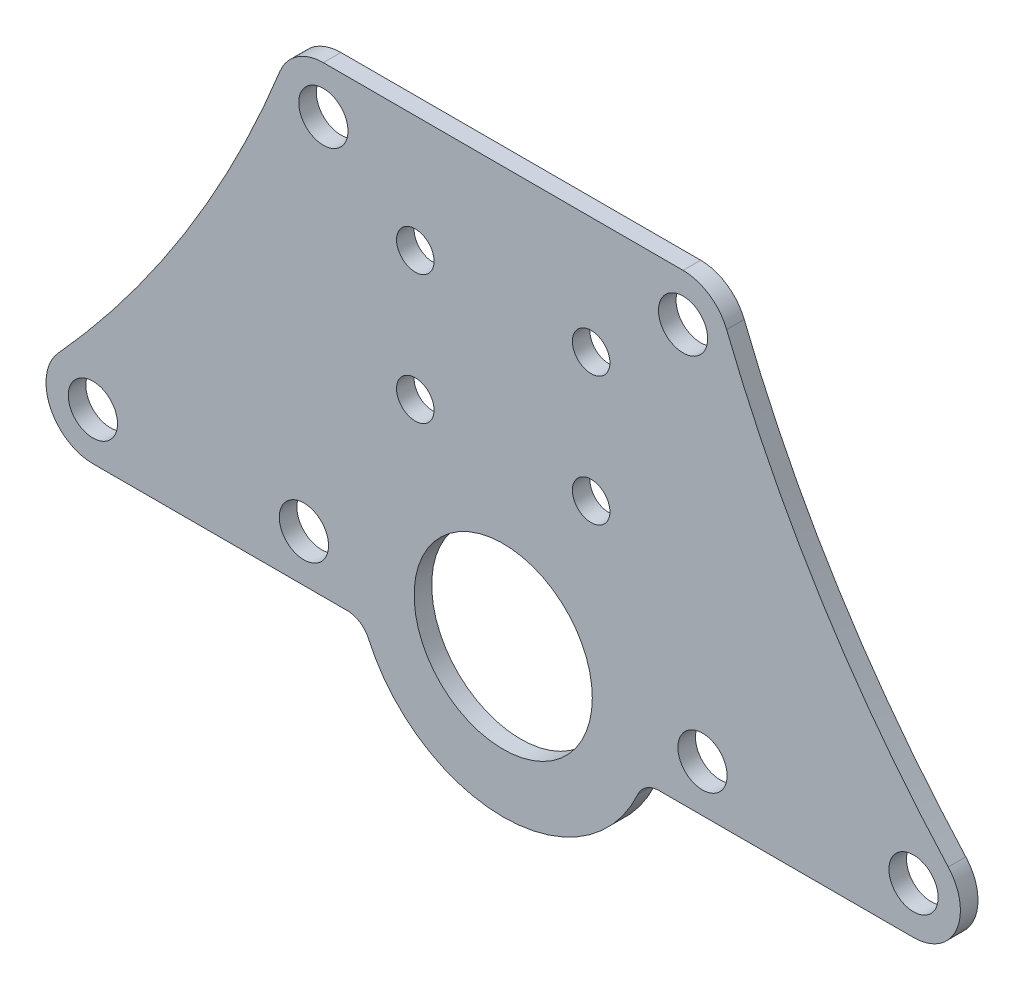
SolidWorks part; units mm, degrees
material "5052-H34"
ref_plane "正面" through (0, 0, 0) normal (0, 0, 1) x (1, 0, 0)
ref_plane "平面" through (0, 0, 0) normal (0, 1, 0) x (1, 0, 0)
ref_plane "右側面" through (0, 0, 0) normal (1, 0, 0) x (0, 0, -1)
sketch "ｽｹｯﾁ1" plane through (0, 0, 0) normal (0, 0, 1) x (1, 0, 0)
  line L0 (0, 5.5) -> (0, 0) construction
  line L1 (-7.5, 5.5) -> (7.5, 5.5) construction
  line L2 (-7.5, 5.5) -> (-7.5, -5.5) construction
  line L3 (-7.5, -5.5) -> (7.5, -5.5) construction
  line L4 (7.5, 5.5) -> (7.5, -5.5) construction
  line L5 (-7.5, 5.5) -> (7.5, -5.5) construction
  line L6 (-7.5, -5.5) -> (7.5, 5.5) construction
  line L7 (0, 0) -> (7.5, 0) construction
  line L8 (0, 0) -> (0, -20) construction
  line L9 (0, -12.5) -> (0, 29.8609) construction
  line L10 (0, -20) -> (35, -20) construction
  line L11 (0, -20) -> (15.343, 11.4578) construction
  line L12 (0, -20) -> (111.9546, 49.957) construction
  line L13 (-35, -24) -> (0, -24)
  line L14 (-15.343, 15.4578) -> (15.343, 15.4578)
  line L15 (0, -24) -> (35, -24)
  circle A0 centre (7.5, 5.5) radius 1.6
  circle A1 centre (-7.5, 5.5) radius 1.6
  circle A2 centre (7.5, -5.5) radius 1.6
  circle A3 centre (-7.5, -5.5) radius 1.6
  circle A4 centre (0, -20) radius 7.6
  circle A5 centre (0, -20) radius 30 construction
  arc A6 (0, 15) -> (5.9222, 14.4953) centre (0, -20) ccw construction
  circle A7 centre (35, -20) radius 2.1
  circle A8 centre (-35, -20) radius 2.1
  circle A9 centre (15.343, 11.4578) radius 2.1
  circle A10 centre (-15.343, 11.4578) radius 2.1
  arc A11 (34.7714, -23.9935) -> (37.9598, -17.3093) centre (35, -20) ccw
  arc A12 (19.0588, 12.9385) -> (14.7529, 15.414) centre (15.343, 11.4578) ccw
  arc A13 (-34.7714, -23.9935) -> (-37.9598, -17.3093) centre (-35, -20) cw
  arc A14 (-19.0588, 12.9385) -> (-14.7529, 15.414) centre (-15.343, 11.4578) cw
  arc A15 (19.0588, 12.9385) -> (37.9598, -17.3093) centre (111.9546, 49.957) ccw
  circle A16 centre (17, -20) radius 2.1
  arc A17 (-19.0588, 12.9385) -> (-37.9598, -17.3093) centre (-111.9546, 49.957) cw
  arc A18 (5.9222, 14.4953) -> (14.7529, 15.414) centre (0, 114.3198) ccw construction
  arc A19 (0, 214.3198) -> (-14.7529, 15.414) centre (0, 114.3198) ccw construction
  arc A20 (60.5335, 193.9169) -> (0, 214.3198) centre (0, 114.3198) ccw construction
  arc A21 (14.7529, 15.414) -> (-14.7529, 15.414) centre (0, 114.3198) ccw construction
  arc A22 (-14.7529, 15.414) -> (60.5335, 193.9169) centre (0, 114.3198) ccw construction
  circle A24 centre (0, -20) radius 12.6
  circle A27 centre (-17, -20) radius 2.1
  arc A30 (-14.7529, 15.414) -> (-5.9222, 14.4953) centre (0, 114.3198) ccw construction
  arc A31 (-5.9222, 14.4953) -> (0, 14.3198) centre (0, 114.3198) ccw construction
  arc A32 (0, 14.3198) -> (5.9222, 14.4953) centre (0, 114.3198) ccw construction
  arc A33 (5.9222, 14.4953) -> (0, 15) centre (0, -20) ccw construction
  arc A37 (-11.6535, 13.003) -> (-18.8321, 9.5017) centre (-15.343, 11.4578) cw construction
  arc A38 (-18.8321, 9.5017) -> (-19.0588, 12.9385) centre (-15.343, 11.4578) cw construction
  arc A39 (-14.7529, 15.414) -> (-11.6535, 13.003) centre (-15.343, 11.4578) cw construction
  arc A40 (13.5895, 7.8626) -> (18.8321, 9.5017) centre (15.343, 11.4578) ccw construction
  arc A41 (18.8321, 9.5017) -> (19.0588, 12.9385) centre (15.343, 11.4578) ccw construction
  arc A42 (11.6535, 13.003) -> (13.5895, 7.8626) centre (15.343, 11.4578) ccw construction
  arc A43 (14.7529, 15.414) -> (11.6535, 13.003) centre (15.343, 11.4578) ccw construction
  arc A44 (34.7714, -16.0065) -> (31, -20) centre (35, -20) ccw construction
  arc A45 (31, -20) -> (34.7714, -23.9935) centre (35, -20) ccw construction
  arc A46 (37.9598, -17.3093) -> (34.7714, -16.0065) centre (35, -20) ccw construction
  arc A47 (-34.7714, -16.0065) -> (-34.7714, -23.9935) centre (-35, -20) cw construction
  arc A48 (-37.9598, -17.3093) -> (-34.7714, -16.0065) centre (-35, -20) cw construction
  point P0 (0, 0)
  dimension "D3" = 3.2
  dimension "D4" = 15.2
  dimension "D6" = 60
  dimension "D7" = 70
  dimension "D8" = 4.2
  dimension "D10" = 8
  dimension "D12" = 18
  dimension "D13" = 100
  dimension "D14" = 25.2
  dimension "D11" = 100
  dimension "D1" = 15
  dimension "D2" = 11
  dimension "D5" = 20
  dimension "D9" = 64
extrude "ﾎﾞｽ - 押し出し1" add sketch "ｽｹｯﾁ1" along normal blind 1.5
fillet "ﾌｨﾚｯﾄ2" radius 2 2 edges at (11.9482, -24, 0.75) (-11.9482, -24, 0.75)
